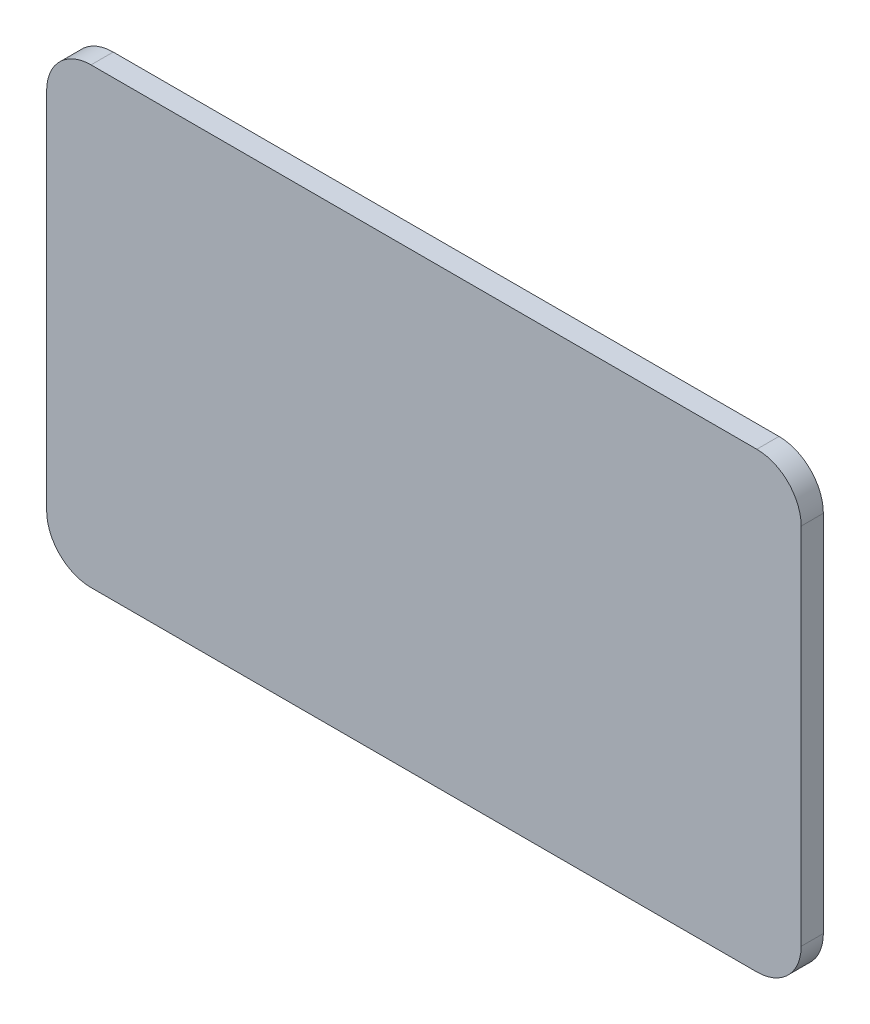
SolidWorks part; units mm, degrees
ref_plane "前视基准面" through (0, 0, 0) normal (0, 0, 1) x (1, 0, 0)
ref_plane "上视基准面" through (0, 0, 0) normal (0, 1, 0) x (1, 0, 0)
ref_plane "右视基准面" through (0, 0, 0) normal (1, 0, 0) x (0, 0, -1)
sketch "草图1" plane through (0, 0, 0) normal (0, 0, 1) x (1, 0, 0)
  line L1 (10, 0) -> (160, 0)
  line L2 (0, 10) -> (0, 92)
  line L3 (10, 102) -> (160, 102)
  line L4 (170, 10) -> (170, 92)
  arc A0 (10, 0) -> (0, 10) centre (10, 10) cw
  arc A1 (160, 0) -> (170, 10) centre (160, 10) ccw
  arc A2 (160, 102) -> (170, 92) centre (160, 92) cw
  arc A3 (0, 92) -> (10, 102) centre (10, 92) cw
  point P7 (0, 0)
  point P10 (170, 0)
  point P15 (0, 102)
  dimension "D3" = 10
  dimension "D1" = 170
  dimension "D2" = 102
extrude "凸台-拉伸1" add sketch "草图1" along normal blind 5
ref_plane "基准面1" through (0, 51, 0) normal (0, -1, 0) x (-1, 0, 0)
ref_plane "基准面2" through (85, 0, 0) normal (1, 0, 0) x (0, 0, -1)
